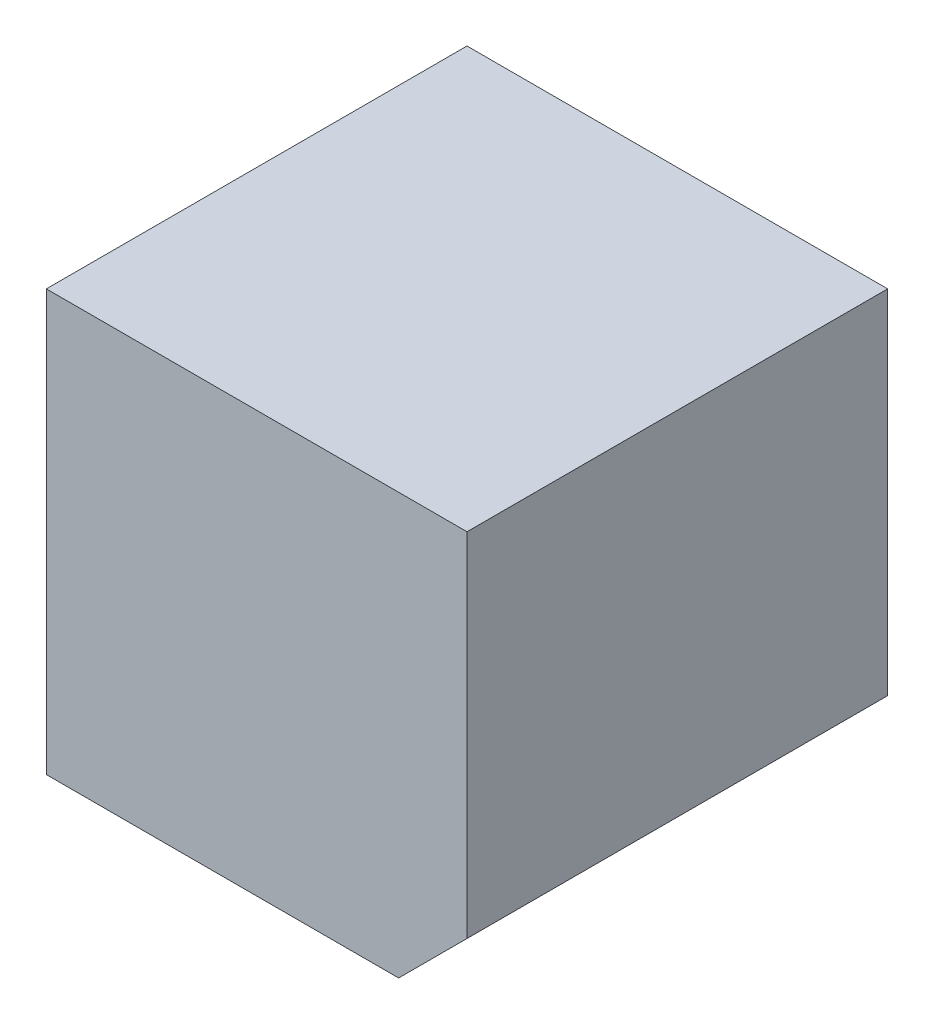
SolidWorks part; units mm, degrees
ref_plane "Plan de face" through (0, 0, 0) normal (0, 0, 1) x (1, 0, 0)
ref_plane "Plan de dessus" through (0, 0, 0) normal (0, 1, 0) x (1, 0, 0)
ref_plane "Plan de droite" through (0, 0, 0) normal (1, 0, 0) x (0, 0, -1)
sketch "Esquisse1" plane through (0, 0, 0) normal (0, 0, 1) x (1, 0, 0)
  line L0 (40, -27) -> (27, -40)
  line L1 (-40, -40) -> (40, -40)
  line L2 (-40, -40) -> (-40, 40)
  line L3 (-40, 40) -> (40, 40)
  line L4 (40, -40) -> (40, 40)
  line L5 (-40, -40) -> (40, 40) construction
  line L6 (-40, 40) -> (40, -40) construction
  point P0 (0, 0)
  dimension "D1" = 67
  dimension "D2" = 80
  dimension "D3" = 67
extrude "Boss.-Extru.1" add sketch "Esquisse1" along normal blind 80 contours L0 L4 L3 L2 L1
sketch "Esquisse2" plane through (0, 0, 0) normal (0, 0, -1) x (-1, 0, 0)
  line L0 (-26.1716, -38) -> (-38, -26.1716)
  line L1 (38, 38) -> (-38, 38)
  line L2 (38, 38) -> (38, -38)
  line L3 (38, -38) -> (-38, -38)
  line L4 (-38, 38) -> (-38, -38)
  line L5 (38, 38) -> (-38, -38) construction
  line L6 (38, -38) -> (-38, 38) construction
  line L7 (-40, -27) -> (-27, -40) construction
  point P0 (0, 0)
  dimension "D1" = 76
  dimension "D2" = 2
  dimension "D3" = 64.1716
extrude "Enlèv. mat.-Extru.1" cut sketch "Esquisse2" against normal blind 78 contours L1 L4 L0 L3 L2
